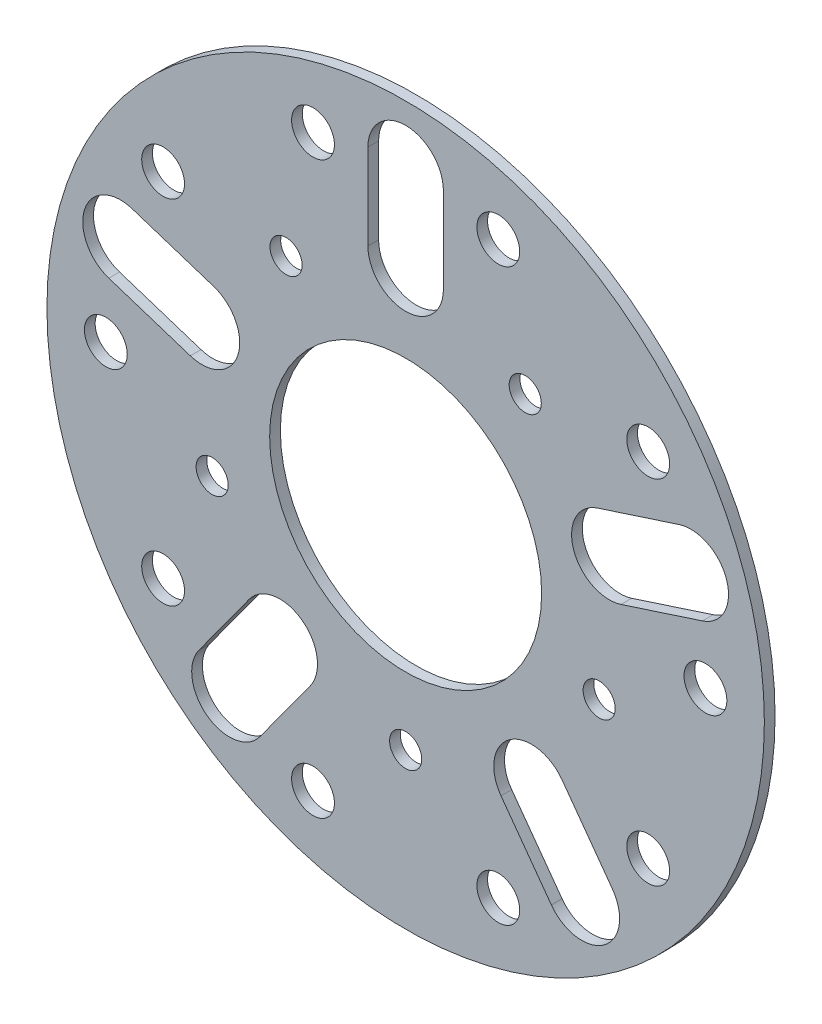
SolidWorks part; units mm, degrees
ref_plane "前视基准面" through (0, 0, 0) normal (0, 0, 1) x (1, 0, 0)
ref_plane "上视基准面" through (0, 0, 0) normal (0, 1, 0) x (1, 0, 0)
ref_plane "右视基准面" through (0, 0, 0) normal (1, 0, 0) x (0, 0, -1)
sketch "草图1" plane through (0, 0, 0) normal (0, 0, 1) x (1, 0, 0)
  line L0 (-18.0701, -5.8713) -> (0, -19) construction
  line L1 (0, 0) -> (-9.035, -12.4357) construction
  line L2 (-9.035, -12.4357) -> (-22.2404, -30.6113) construction
  line L3 (0, 0) -> (0, -44.5087) construction
  line L4 (0, 0) -> (-14.8252, -45.6273) construction
  line L5 (-16.458, -22.6525) -> (-11.7557, -16.1803) construction
  line L8 (-19.3088, -20.5812) -> (-14.6065, -14.1091)
  line L11 (-13.6072, -24.7237) -> (-8.9049, -18.2516)
  line L14 (-26.6296, 8.6525) -> (-19.0211, 6.1803) construction
  line L17 (-25.5407, 12.0038) -> (-17.9322, 9.5317)
  line L20 (-27.7185, 5.3011) -> (-20.1101, 2.829)
  line L21 (0, 28) -> (0, 20) construction
  line L22 (3.5238, 28) -> (3.5238, 20)
  line L23 (-3.5238, 28) -> (-3.5238, 20)
  line L24 (26.6296, 8.6525) -> (19.0211, 6.1803) construction
  line L25 (27.7185, 5.3011) -> (20.1101, 2.829)
  line L26 (25.5407, 12.0038) -> (17.9322, 9.5317)
  line L27 (16.458, -22.6525) -> (11.7557, -16.1803) construction
  line L28 (13.6072, -24.7237) -> (8.9049, -18.2516)
  line L29 (19.3088, -20.5812) -> (14.6065, -14.1091)
  circle A0 centre (0, 0) radius 12.7
  circle A1 centre (0, 0) radius 19 construction
  circle A2 centre (0, 0) radius 28 construction
  circle A3 centre (0, -19) radius 1.5
  circle A4 centre (-18.0701, -5.8713) radius 1.5
  circle A5 centre (-11.1679, 15.3713) radius 1.5
  circle A6 centre (11.1679, 15.3713) radius 1.5
  circle A7 centre (18.0701, -5.8713) radius 1.5
  circle A8 centre (-8.6518, -26.6274) radius 2
  circle A13 centre (-16.458, -22.6525) radius 2 construction
  circle A14 centre (8.6518, -26.6274) radius 2
  circle A15 centre (-27.9977, 0) radius 2
  circle A16 centre (-22.6506, -16.4567) radius 2
  circle A17 centre (-8.6518, 26.6274) radius 2
  circle A18 centre (-22.6506, 16.4567) radius 2
  circle A19 centre (22.6506, 16.4567) radius 2
  circle A20 centre (8.6518, 26.6274) radius 2
  circle A21 centre (22.6506, -16.4567) radius 2
  circle A22 centre (27.9977, 0) radius 2
  circle A23 centre (0, 0) radius 33.5
  circle A34 centre (0, 0) radius 20 construction
  arc A35 (-19.3088, -20.5812) -> (-13.6072, -24.7237) centre (-16.458, -22.6525) ccw
  arc A36 (-8.9049, -18.2516) -> (-14.6065, -14.1091) centre (-11.7557, -16.1803) ccw
  arc A37 (-25.5407, 12.0038) -> (-27.7185, 5.3011) centre (-26.6296, 8.6525) ccw
  arc A38 (-20.1101, 2.829) -> (-17.9322, 9.5317) centre (-19.0211, 6.1803) ccw
  arc A39 (3.5238, 28) -> (-3.5238, 28) centre (0, 28) ccw
  arc A40 (-3.5238, 20) -> (3.5238, 20) centre (0, 20) ccw
  arc A41 (27.7185, 5.3011) -> (25.5407, 12.0038) centre (26.6296, 8.6525) ccw
  arc A42 (17.9322, 9.5317) -> (20.1101, 2.829) centre (19.0211, 6.1803) ccw
  arc A43 (13.6072, -24.7237) -> (19.3088, -20.5812) centre (16.458, -22.6525) ccw
  arc A44 (14.6065, -14.1091) -> (8.9049, -18.2516) centre (11.7557, -16.1803) ccw
  point P27 (-14.1068, -19.4164)
  point P53 (-22.8254, 7.4164)
  point P60 (0, 24)
  point P67 (22.8254, 7.4164)
  point P74 (14.1068, -19.4164)
  dimension "D1" = 25.4
  dimension "D2" = 38
  dimension "D3" = 56
  dimension "D4" = 3
  dimension "D7" = 4
  dimension "D9" = 67
  dimension "D10" = 40
  dimension "D6" = 18
  dimension "D5" = 5
  dimension "D8" = 5
  dimension "D11" = 5
extrude "凸台-拉伸1" add sketch "草图1" along normal blind 1 contours A23
